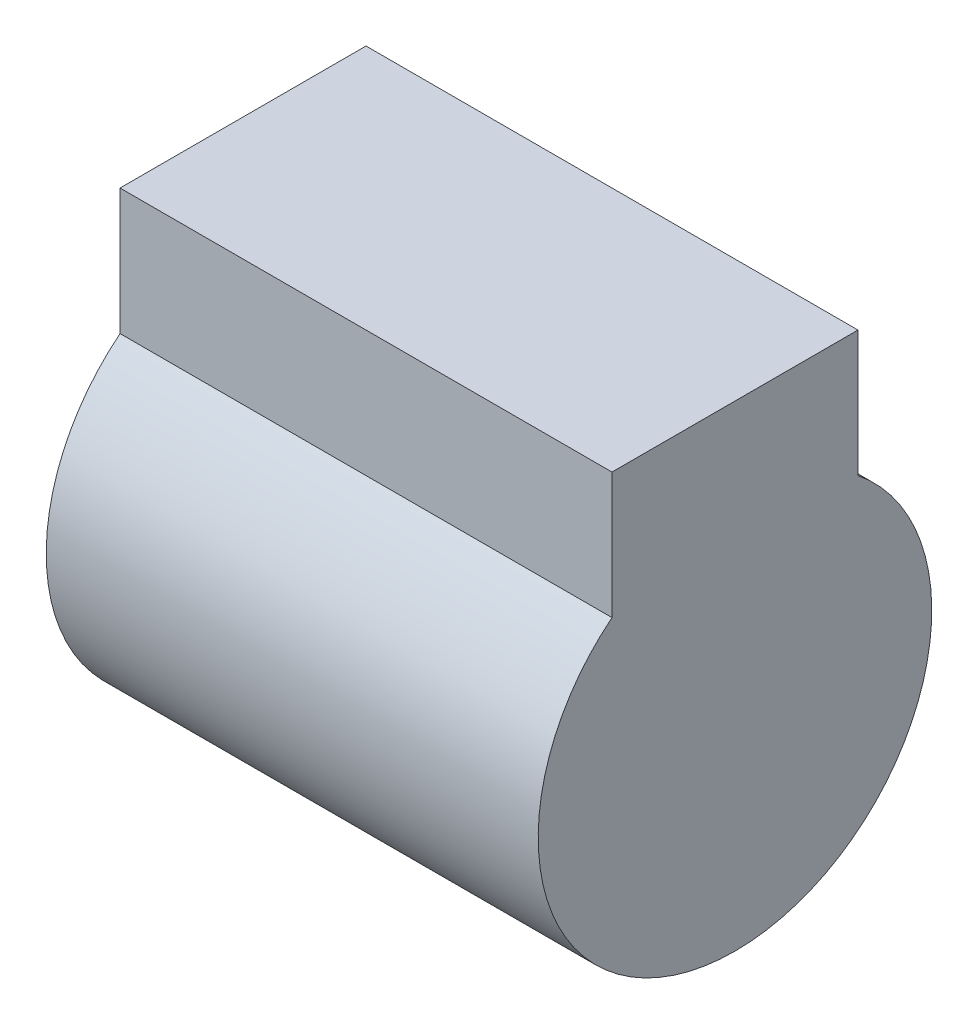
SolidWorks part; units mm, degrees
ref_plane "Front Plane" through (0, 0, 0) normal (0, 0, 1) x (1, 0, 0)
ref_plane "Top Plane" through (0, 0, 0) normal (0, 1, 0) x (1, 0, 0)
ref_plane "Right Plane" through (0, 0, 0) normal (1, 0, 0) x (0, 0, -1)
sketch "Sketch2" plane through (0, 0, 0) normal (1, 0, 0) x (0, 0, -1)
  circle A0 centre (0, 0) radius 16
extrude "Boss-Extrude1" add sketch "Sketch2" along normal blind 40 contours A0
sketch "Sketch3" plane through (0, 0, 0) normal (1, 0, 0) x (0, 0, -1)
  circle A0 centre (0, 0) radius 3.75
extrude "Cut-Extrude1" cut sketch "Sketch3" along normal blind 8.5
sketch "Sketch4" plane through (0, 0, 0) normal (1, 0, 0) x (0, 0, -1)
  line L0 (4.9329, 12.49) -> (10, 12.49)
  line L1 (10, 12.49) -> (-10, 12.49)
  line L2 (-10, 12.49) -> (-10, 15.8222)
  line L5 (10, 12.49) -> (10, 22.7394)
  line L6 (10, 22.7394) -> (-10, 22.7394)
  line L7 (-10, 22.7394) -> (-10, 15.8222)
  circle A0 centre (0, 0) radius 16 construction
extrude "Boss-Extrude3" add sketch "Sketch4" along normal through all contours L5 L6 L7 L2 L1
